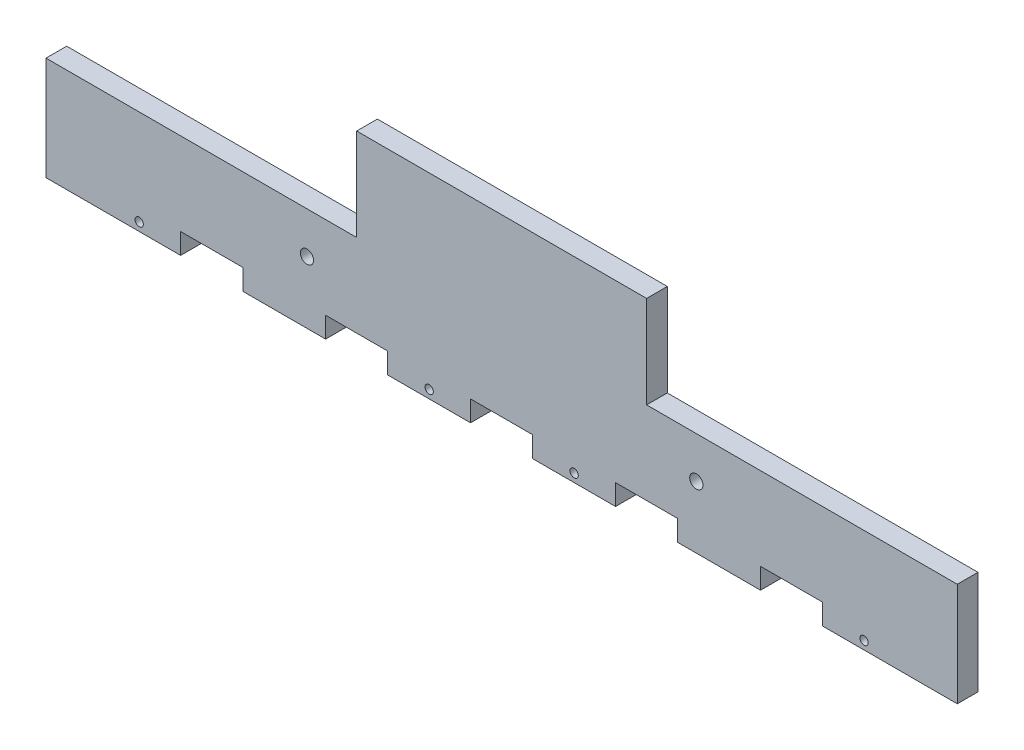
SolidWorks part; units mm, degrees
ref_plane "Front" through (0, 0, 0) normal (0, 0, 1) x (1, 0, 0)
ref_plane "Top" through (0, 0, 0) normal (0, 1, 0) x (1, 0, 0)
ref_plane "Right" through (0, 0, 0) normal (1, 0, 0) x (0, 0, -1)
sketch "草图1" plane through (0, 0, 0) normal (0, 0, 1) x (1, 0, 0)
  line L1 (0, 0) -> (220, 0)
  line L2 (0, 0) -> (0, 25)
  line L3 (0, 25) -> (220, 25)
  line L4 (220, 0) -> (220, 25)
  dimension "D1" = 25
  dimension "D2" = 220
extrude "凸台-拉伸1" add sketch "草图1" along normal blind 5
sketch "草图2" plane through (0, 0, 5) normal (0, 0, 1) x (1, 0, 0)
  line L0 (220, 25) -> (0, 25) construction
  line L1 (75, 25) -> (145, 25)
  line L2 (75, 25) -> (75, 47.2635)
  line L3 (75, 47.2635) -> (145, 47.2635)
  line L4 (145, 25) -> (145, 47.2635)
  line L5 (0, 0) -> (220, 0) construction
  point P6 (110, 47.2635)
  point P9 (110, 0)
  dimension "D1" = 70
  dimension "D2" = 0
extrude "凸台-拉伸2" add sketch "草图2" against normal blind 5
sketch "草图3" plane through (0, 0, 5) normal (0, 0, 1) x (1, 0, 0)
  line L0 (0, 0) -> (220, 0) construction
  line L1 (102.5, 0) -> (117.5, 0)
  line L2 (102.5, 0) -> (102.5, 5)
  line L3 (102.5, 5) -> (117.5, 5)
  line L4 (117.5, 0) -> (117.5, 5)
  line L5 (145, 47.2635) -> (75, 47.2635) construction
  line L7 (137.5, 0) -> (152.5, 0)
  line L8 (137.5, 0) -> (137.5, 5)
  line L9 (137.5, 5) -> (152.5, 5)
  line L10 (152.5, 0) -> (152.5, 5)
  line L11 (172.5, 0) -> (187.5, 0)
  line L12 (172.5, 0) -> (172.5, 5)
  line L13 (172.5, 5) -> (187.5, 5)
  line L14 (187.5, 0) -> (187.5, 5)
  line L15 (82.5, 0) -> (67.5, 0)
  line L16 (82.5, 0) -> (82.5, 5)
  line L17 (82.5, 5) -> (67.5, 5)
  line L18 (67.5, 0) -> (67.5, 5)
  line L19 (32.5, 0) -> (47.5, 0)
  line L20 (32.5, 0) -> (32.5, 5)
  line L21 (32.5, 5) -> (47.5, 5)
  line L22 (47.5, 0) -> (47.5, 5)
  point P6 (110, 5)
  point P9 (110, 47.2635)
  dimension "D1" = 15
  dimension "D2" = 5
  dimension "D3" = 0
  dimension "D4" = 15
  dimension "D5" = 15
  dimension "D6" = 15
  dimension "D7" = 15
  dimension "D8" = 20
  dimension "D9" = 20
  dimension "D10" = 20
  dimension "D11" = 20
extrude "切除-拉伸1" cut sketch "草图3" against normal through all
sketch "草图4" plane through (0, 0, 5) normal (0, 0, 1) x (1, 0, 0)
  line L0 (145, 47.2635) -> (75, 47.2635) construction
  line L3 (75, 25) -> (0, 25) construction
  line L4 (220, 25) -> (145, 25) construction
  circle A0 centre (63, 15) radius 1.6
  circle A1 centre (157, 15) radius 1.6
  point P4 (110, 47.2635)
  dimension "D1" = 47
  dimension "D2" = 10
  dimension "D3" = 47
  dimension "D4" = 10
extrude "切除-拉伸2" cut sketch "草图4" against normal through all
sketch "草图7" plane through (0, 0, 5) normal (0, 0, 1) x (1, 0, 0)
  line L0 (0, 0) -> (32.5, 0) construction
  line L1 (32.5, 5) -> (32.5, 0) construction
  line L2 (187.5, 0) -> (187.5, 5) construction
  circle A0 centre (22.5, 2) radius 1
  circle A1 centre (92.5, 2) radius 1
  circle A2 centre (127.5, 2) radius 1
  circle A3 centre (197.5, 2) radius 1
  dimension "D1" = 2
  dimension "D2" = 2
  dimension "D3" = 10
  dimension "D4" = 10
extrude "切除-拉伸4" cut sketch "草图7" against normal through all
